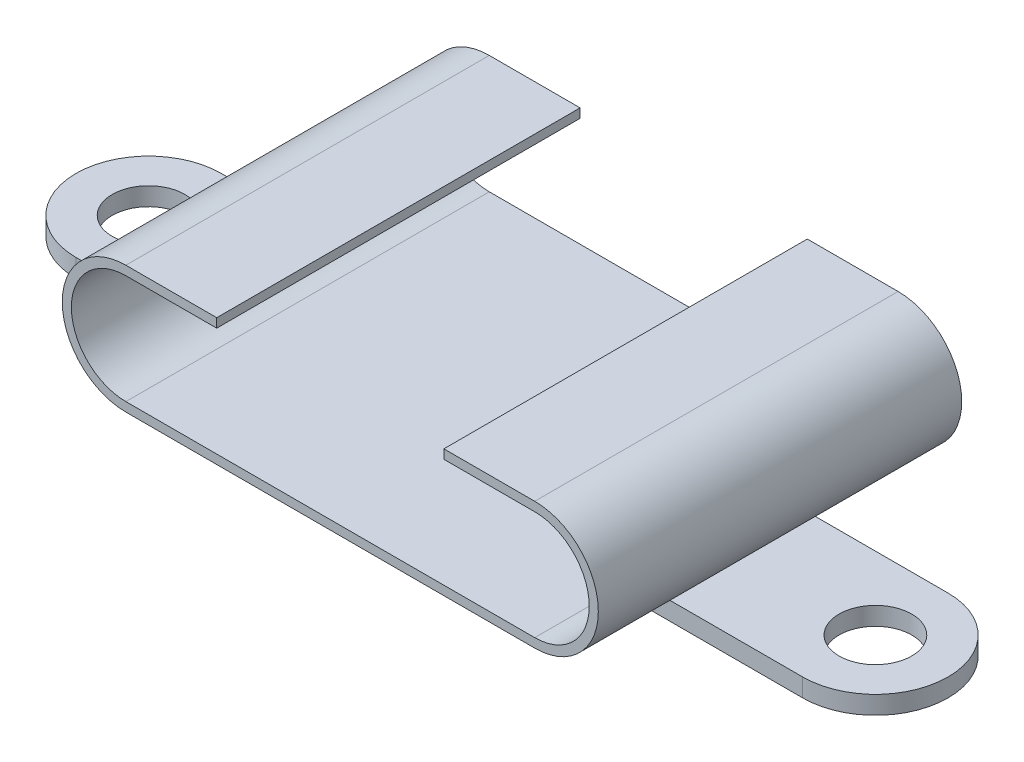
SolidWorks part; units mm, degrees
ref_plane "Plan de face" through (0, 0, 0) normal (0, 0, 1) x (1, 0, 0)
ref_plane "Plan de dessus" through (0, 0, 0) normal (0, 1, 0) x (1, 0, 0)
ref_plane "Plan de droite" through (0, 0, 0) normal (1, 0, 0) x (0, 0, -1)
sketch "Esquisse1" plane through (0, 0, 0) normal (0, 0, 1) x (1, 0, 0)
  line L0 (0, 0) -> (45, 0) construction
  line L1 (0, 7) -> (45, 7)
  line L2 (0, -7) -> (45, -7)
  arc A0 (0, 7) -> (0, -7) centre (0, 0) ccw
  arc A1 (45, -7) -> (45, 7) centre (45, 0) ccw
  point P3 (22.5, 0)
  dimension "D2" = 7
  dimension "D1" = 45
extrude "Boss.-Extru.1" add sketch "Esquisse1" along normal blind 40
sketch "Esquisse2" plane through (0, 0, 40) normal (0, 0, 1) x (1, 0, 0)
  line L4 (0, -6) -> (45, -6)
  line L5 (45, 6) -> (0, 6)
  line L6 (0, -6) -> (45, -6)
  line L7 (45, 6) -> (0, 6)
  arc A4 (0, 6) -> (0, -6) centre (0, 0) ccw
  arc A5 (45, -6) -> (45, 6) centre (45, 0) ccw
  arc A6 (0, 6) -> (0, -6) centre (0, 0) ccw
  arc A7 (45, -6) -> (45, 6) centre (45, 0) ccw
  dimension "D1" = 1
extrude "Enlèv. mat.-Extru.1" cut sketch "Esquisse2" against normal through all
sketch "Esquisse3" plane through (0, 7, 0) normal (0, 1, 0) x (1, 0, 0)
  line L0 (22.5, 0) -> (22.5, -40) construction
  line L1 (45, 0) -> (0, 0) construction
  line L2 (45, -40) -> (0, -40) construction
  line L3 (35.0019, 0) -> (35.0019, -40)
  line L4 (9.9981, 0) -> (9.9981, -40)
  line L5 (9.9981, 0) -> (35.0019, 0)
  line L6 (35.0019, -40) -> (9.9981, -40)
  dimension "D1" = 12.5019
extrude "Enlèv. mat.-Extru.2" cut sketch "Esquisse3" against normal up to surface (1 mm away) up to face at (22.5, 6, 20)
sketch "Esquisse4" plane through (0, -7, 0) normal (0, -1, 0) x (-1, 0, 0)
  line L0 (-62.5, -20) -> (17.5, -20) construction
  line L3 (-62.5, -12) -> (17.5, -12)
  line L4 (-62.5, -28) -> (17.5, -28)
  line L5 (-22.5, 0) -> (-22.5, -40) construction
  line L6 (0, 0) -> (-45, 0) construction
  line L7 (0, -40) -> (-45, -40) construction
  arc A0 (-62.5, -12) -> (-62.5, -28) centre (-62.5, -20) ccw
  arc A1 (17.5, -28) -> (17.5, -12) centre (17.5, -20) ccw
  circle A2 centre (17.5, -20) radius 4
  circle A3 centre (-62.5, -20) radius 4
  point P2 (-22.5, -20)
  dimension "D2" = 8
  dimension "D3" = 8
  dimension "D1" = 80
extrude "Boss.-Extru.2" add sketch "Esquisse4" along normal blind 2
